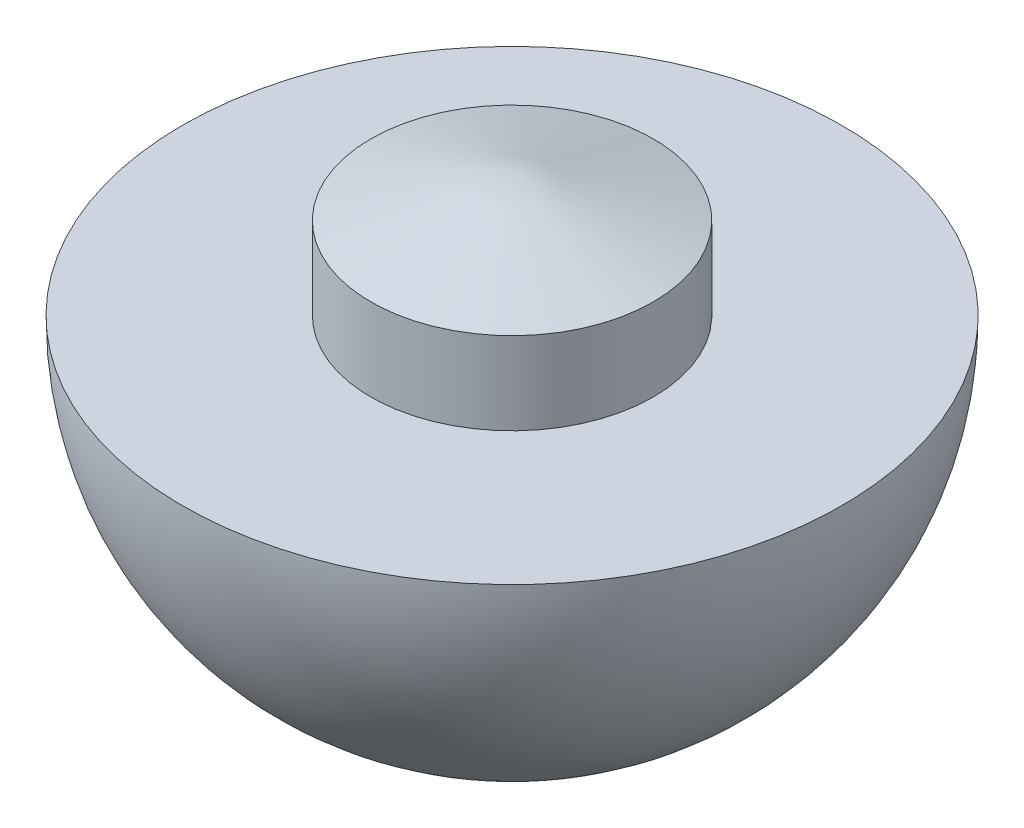
SolidWorks part; units mm, degrees
ref_plane "Front Plane" through (0, 0, 0) normal (0, 0, 1) x (1, 0, 0)
ref_plane "Top Plane" through (0, 0, 0) normal (0, 1, 0) x (1, 0, 0)
ref_plane "Right Plane" through (0, 0, 0) normal (1, 0, 0) x (0, 0, -1)
sketch "Sketch1" plane through (0, 0, 0) normal (0, 0, 1) x (1, 0, 0)
  line L0 (-1.778, 1.1049) -> (0.254, 1.1049)
  line L1 (0.254, 1.1049) -> (0.254, 1.9939)
  line L2 (1.778, 2.4511) -> (1.778, -2.4511)
  line L3 (0.254, 1.9939) -> (1.778, 2.4511)
  arc A1 (-1.778, 1.1049) -> (1.778, -2.4511) centre (1.778, 1.1049) ccw
  dimension "D1" = 3.556
revolve "Revolve1" add sketch "Sketch1" angle 360 about L2
